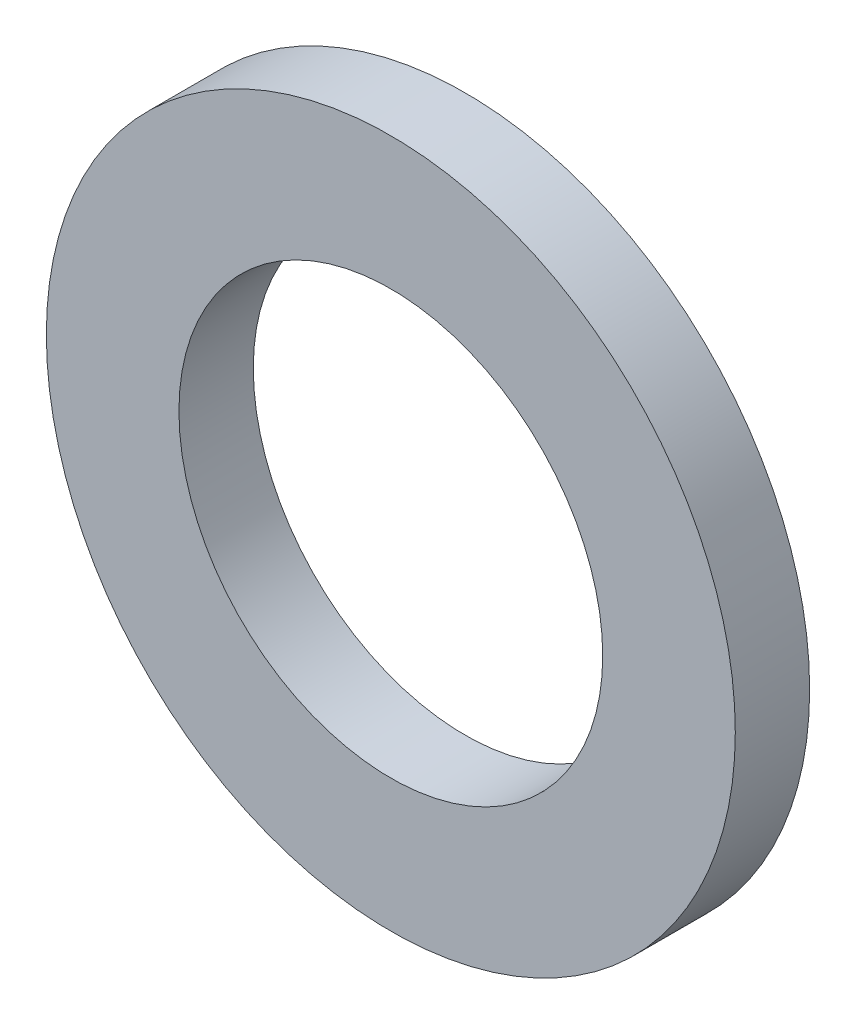
SolidWorks part; units mm, degrees
material "SPRING STEEL ASTM A 229"
ref_plane "Front Plane" through (0, 0, 0) normal (0, 0, 1) x (1, 0, 0)
ref_plane "Top Plane" through (0, 0, 0) normal (0, 1, 0) x (1, 0, 0)
ref_plane "Right Plane" through (0, 0, 0) normal (1, 0, 0) x (0, 0, -1)
sketch "Sketch1" plane through (0, 0, 0) normal (1, 0, 0) x (0, 0, -1)
  line L0 (0, 0) -> (44.392, 0) construction
  line L1 (0, 0) -> (0, 32.1562) construction
  line L3 (-1.5, 13.9) -> (1.5, 13.9)
  line L4 (-1.5, 13.9) -> (-1.5, 8.55)
  line L5 (-1.5, 8.55) -> (1.5, 8.55)
  line L6 (1.5, 13.9) -> (1.5, 8.55)
  dimension "D1" = 27.8
  dimension "D2" = 17.1
  dimension "D3" = 3
revolve "Revolve1" add sketch "Sketch1" angle 360 about L0
